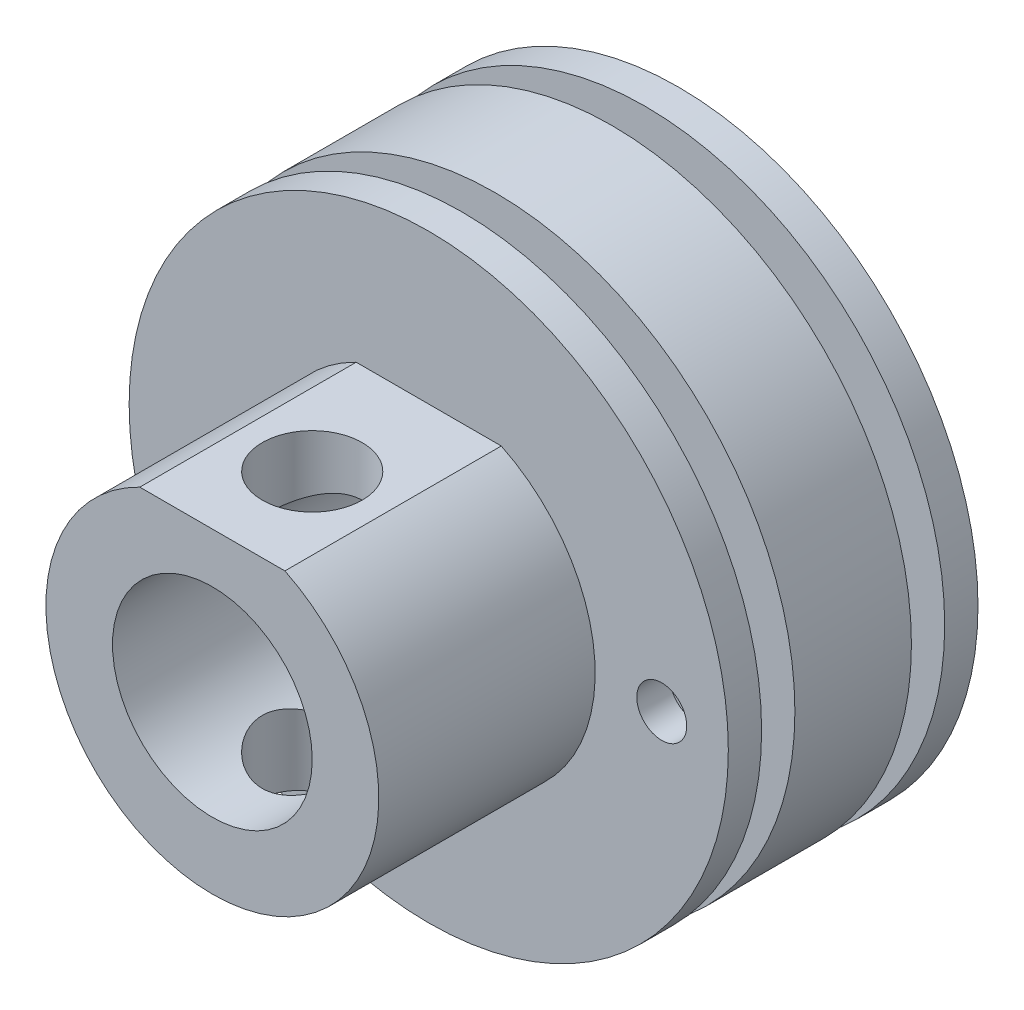
SolidWorks part; units mm, degrees
material "6061 合金"
ref_plane "前视基准面" through (0, 0, 0) normal (0, 0, 1) x (1, 0, 0)
ref_plane "上视基准面" through (0, 0, 0) normal (0, 1, 0) x (1, 0, 0)
ref_plane "右视基准面" through (0, 0, 0) normal (1, 0, 0) x (0, 0, -1)
sketch "草图1" plane through (0, 0, 0) normal (0, 0, 1) x (1, 0, 0)
  circle A0 centre (0, 0) radius 9
  dimension "D1" = 18
extrude "凸台-拉伸1" add sketch "草图1" along normal blind 7.5
sketch "草图2" plane through (0, 0, 7.5) normal (0, 0, 1) x (1, 0, 0)
  circle A0 centre (0, 0) radius 5
  dimension "D1" = 10
extrude "凸台-拉伸2" add sketch "草图2" along normal blind 6.5
sketch "草图3" plane through (0, 0, 14) normal (0, 0, 1) x (1, 0, 0)
  circle A0 centre (0, 0) radius 3
  dimension "D1" = 6
extrude "切除-拉伸1" cut sketch "草图3" against normal through all
sketch "草图4" plane through (0, 0, 0) normal (0, 1, 0) x (1, 0, 0)
  line L0 (-5, -14) -> (5, -14) construction
  circle A0 centre (0, -11) radius 1.5
  dimension "D1" = 3
  dimension "D2" = 3
extrude "切除-拉伸2" cut sketch "草图4" against normal through all both and the other way through all
cosmetic thread "装饰螺纹线1" parameters "D1"=29.9999, "D2"=4
sketch "草图5" plane through (0, 0, 0) normal (0, 1, 0) x (1, 0, 0)
  line L1 (0, 0.803) -> (0, -7.5) construction
  line L2 (9, -1) -> (5, -1)
  line L3 (9, -1) -> (9, -2)
  line L4 (9, -2) -> (5, -2)
  line L5 (5, -1) -> (5, -2)
  line L6 (-5, -7.5) -> (5, -7.5) construction
  line L8 (9, 0) -> (-9, 0) construction
  line L9 (9, -7.5) -> (9, 0) construction
  line L10 (9, -5.5) -> (5, -5.5)
  line L11 (9, -5.5) -> (9, -6.5)
  line L12 (9, -6.5) -> (5, -6.5)
  line L13 (5, -5.5) -> (5, -6.5)
  line L14 (-9, -7.5) -> (9, -7.5) construction
  dimension "D1" = 1
  dimension "D2" = 1
  dimension "D4" = 4
  dimension "D5" = 1
  dimension "D6" = 1
revolve "切除-旋转1" cut sketch "草图5" angle 360 about L1
sketch "草图6" plane through (0, 0, 7.5) normal (0, 0, 1) x (1, 0, 0)
  circle A0 centre (7, 0) radius 0.75
  circle A1 centre (0, 0) radius 7 construction
  dimension "D1" = 14
  dimension "D2" = 1.5
extrude "切除-拉伸3" cut sketch "草图6" against normal blind 10
sketch "草图8" plane through (0, 0, 0) normal (1, 0, 0) x (0, 0, -1)
  line L0 (-14, 5) -> (-14, -5) construction
  line L1 (-7.5, 5) -> (-14, 5)
  line L2 (-7.5, 5) -> (-7.5, 4.5)
  line L3 (-7.5, 4.5) -> (-14, 4.5)
  line L4 (-14, 5) -> (-14, 4.5)
  line L5 (-7.5, 5) -> (-14, 4.5) construction
  line L6 (-7.5, 4.5) -> (-14, 5) construction
  point P4 (-10.75, 4.75)
  dimension "D1" = 0.5
extrude "切除-拉伸4" cut sketch "草图8" along normal through all both and the other way through all
